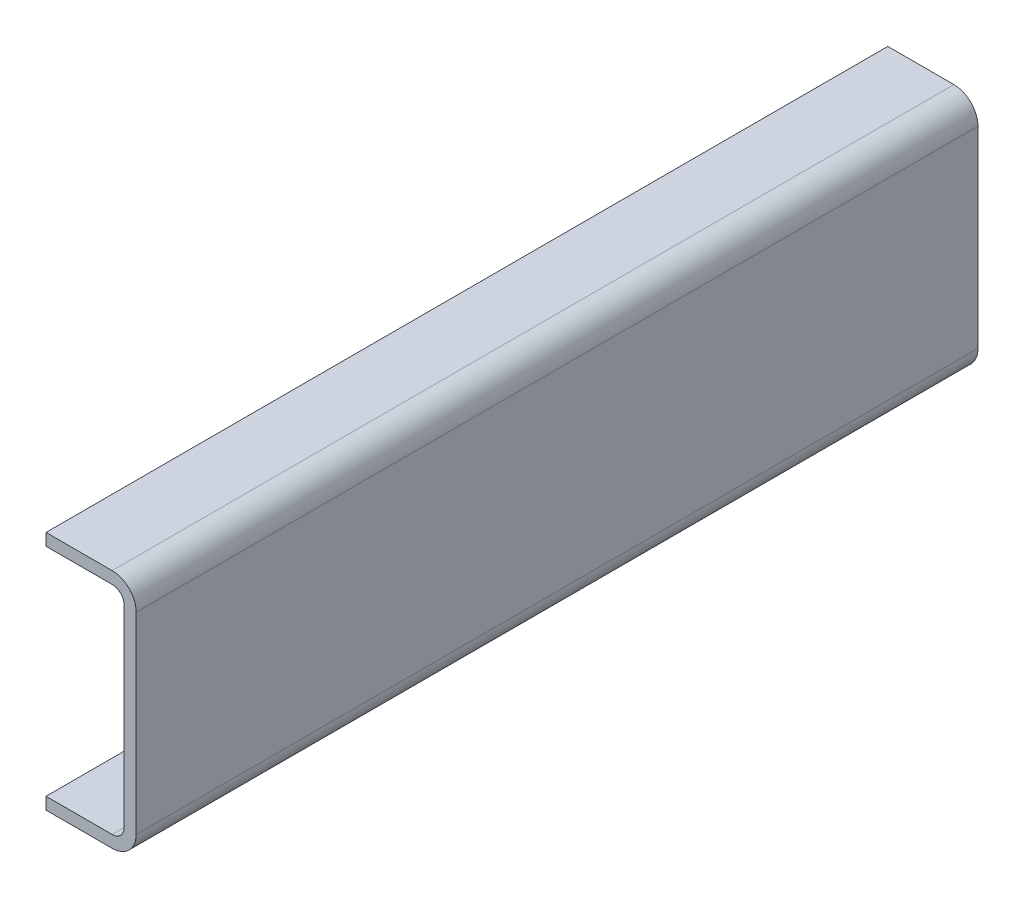
SolidWorks part; units mm, degrees
ref_plane "Front Plane" through (0, 0, 0) normal (0, 0, 1) x (1, 0, 0)
ref_plane "Top Plane" through (0, 0, 0) normal (0, 1, 0) x (1, 0, 0)
ref_plane "Right Plane" through (0, 0, 0) normal (1, 0, 0) x (0, 0, -1)
sketch "Sketch1" plane through (0, 0, 0) normal (0, 0, 1) x (1, 0, 0)
  line L0 (0, 2.54) -> (0, 22.86)
  line L1 (-2.54, 25.4) -> (-9.525, 25.4)
  line L2 (-2.54, 0) -> (-9.525, 0)
  line L3 (-2.54, 1.27) -> (-9.525, 1.27)
  line L4 (-1.27, 2.54) -> (-1.27, 22.86)
  line L5 (-2.54, 24.13) -> (-9.525, 24.13)
  line L6 (-9.525, 25.4) -> (-9.525, 24.13)
  line L7 (-9.525, 1.27) -> (-9.525, 0)
  arc A0 (0, 2.54) -> (-2.54, 0) centre (-2.54, 2.54) cw
  arc A1 (0, 22.86) -> (-2.54, 25.4) centre (-2.54, 22.86) ccw
  arc A2 (-1.27, 2.54) -> (-2.54, 1.27) centre (-2.54, 2.54) cw
  arc A3 (-1.27, 22.86) -> (-2.54, 24.13) centre (-2.54, 22.86) ccw
  point P7 (0, 0)
  point P10 (0, 25.4)
  dimension "D3" = 2.54
  dimension "D1" = 9.525
  dimension "D2" = 25.4
  dimension "D4" = 1.27
extrude "Boss-Extrude1" add sketch "Sketch1" along normal blind 88.9
equation "\"Length\"=4.5"
equation "\"D1@Boss-Extrude1\"=\"Set_Length\""
